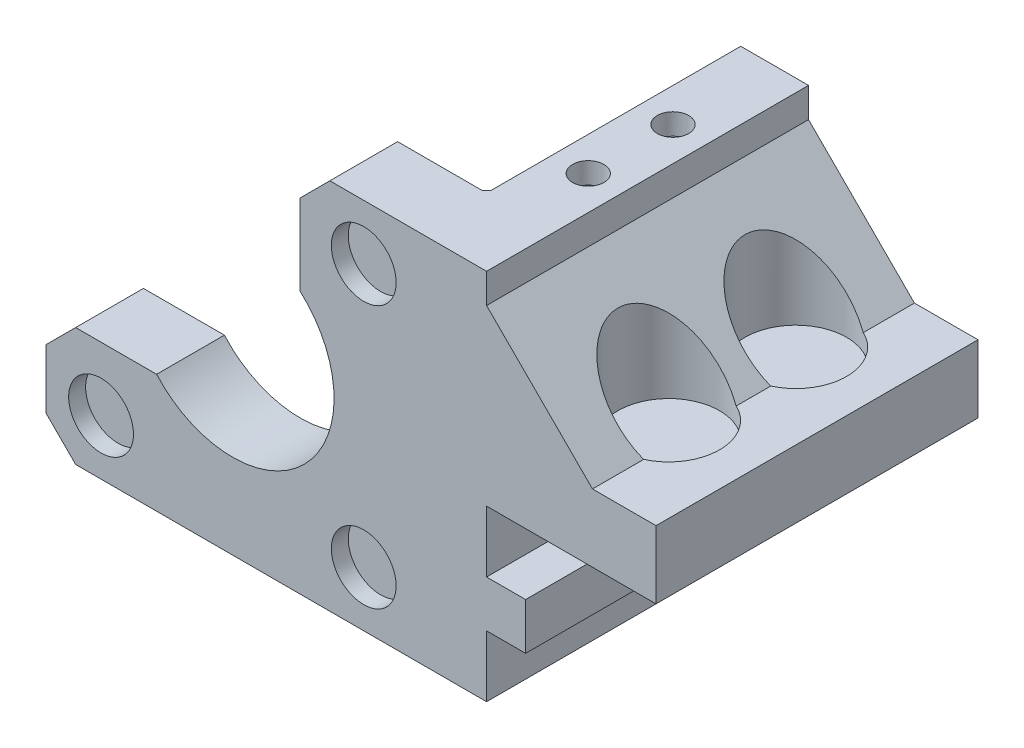
SolidWorks part; units mm, degrees
ref_plane "Front Plane" through (0, 0, 0) normal (0, 0, 1) x (1, 0, 0)
ref_plane "Top Plane" through (0, 0, 0) normal (0, 1, 0) x (1, 0, 0)
ref_plane "Right Plane" through (0, 0, 0) normal (1, 0, 0) x (0, 0, -1)
sketch "Sketch1" plane through (0, 0, 0) normal (0, 0, 1) x (1, 0, 0)
  line L0 (-22, -8) -> (-8.9443, -8)
  line L1 (8, 22) -> (22, 22)
  line L2 (-22, -8) -> (-22, -22)
  line L3 (-22, -22) -> (22, -22)
  line L4 (22, 22) -> (22, -22)
  line L5 (-20, 20) -> (22, -22) construction
  line L6 (-22, -22) -> (22, 22) construction
  line L7 (8, 8.9443) -> (8, 22)
  line L8 (36.9982, -22) -> (31, -22) construction
  arc A0 (-8.9443, -8) -> (8, 8.9443) centre (0, 0) ccw
  circle A1 centre (-15.5, 15.5) radius 1.85 construction
  circle A2 centre (15.5, 15.5) radius 1.85
  circle A3 centre (15.5, -15.5) radius 1.85
  circle A4 centre (-15.5, -15.5) radius 1.85
  dimension "D1" = 3.7
  dimension "D9" = 24
  dimension "D10" = 14
  dimension "D2" = 15.5
  dimension "D3" = 15.5
  dimension "D6" = 31
  dimension "D7" = 31
  dimension "D8" = 44
  dimension "D11" = 22
  dimension "D4" = 2
  dimension "D5" = 2
extrude "Boss-Extrude1" add sketch "Sketch1" along normal blind 8 contours A0 L0 L2 L3 L4 L1 L7 A4 A3 A2
sketch "Sketch3" plane through (0, 0, 8) normal (0, 0, 1) x (1, 0, 0)
  line L0 (30, -9.25) -> (30, -2)
  line L1 (22, -22) -> (30, -22)
  line L2 (22, 22) -> (30, 22)
  line L3 (22, 22) -> (22, 6)
  line L4 (30, -22) -> (30, -14.75)
  line L5 (30, 6) -> (50, 6)
  line L6 (22, 6) -> (22, -22)
  line L7 (30, -2) -> (50, -2)
  line L8 (50, 6) -> (50, -2)
  line L9 (30, -9.25) -> (34.6066, -9.25)
  line L10 (30, 22) -> (30, 6)
  line L12 (30, -14.75) -> (34.6066, -14.75)
  line L13 (34.6066, -9.25) -> (34.6066, -14.75)
  dimension "D1" = 20
  dimension "D2" = 20
  dimension "D3" = 8
  dimension "D4" = 8
  dimension "D5" = 5.5
extrude "Boss-Extrude3" add sketch "Sketch3" against normal blind 38
chamfer "Chamfer1" distance 3.5 angle 45 3 edges at (8, 22, 4) (-22, -8, 4) (-22, -22, 4)
chamfer "Chamfer2" distance 12.5 angle 45 1 edges at (30, 6, -11)
sketch "Sketch4" plane through (0, -2, 0) normal (0, -1, 0) x (1, 0, 0)
  line L3 (50, -30) -> (50, 8) construction
  circle A0 centre (40, -3.5) radius 2.825
  circle A1 centre (40, -18.5) radius 2.825
  point P8 (50, -11)
  dimension "D2" = 5.65
  dimension "D1" = 15
  dimension "D3" = 7.5
extrude "Cut-Extrude1" cut sketch "Sketch4" against normal blind 15
sketch "Sketch5" plane through (0, 6, 0) normal (0, 1, 0) x (1, 0, 0)
  circle A0 centre (40, 18.5) radius 6
  circle A1 centre (40, 3.5) radius 6
  dimension "D1" = 12
extrude "Cut-Extrude2" cut sketch "Sketch5" along normal blind 15 from offset 2 offset against normal yes
chamfer "Chamfer3" distance 0.5 angle 45 1 edges at (22, 0, 0)
sketch "Sketch6" plane through (0, 0, 8) normal (0, 0, 1) x (1, 0, 0)
  circle A0 centre (15.5, 15.5) radius 3.825
  circle A1 centre (15.5, -15.5) radius 3.825
  circle A2 centre (-15.5, -15.5) radius 3.825
  dimension "D1" = 7.65
extrude "Cut-Extrude3" cut sketch "Sketch6" against normal blind 2
sketch "Sketch10" plane through (0, 22, 0) normal (0, 1, 0) x (1, 0, 0)
  line L0 (11.5, 0) -> (21.5, 0) construction
  line L1 (30, 30) -> (30, -8) construction
  circle A0 centre (26, 8) radius 1.85
  circle A1 centre (26, 18) radius 1.85
  dimension "D2" = 3.7
  dimension "D1" = 10
  dimension "D3" = 18
  dimension "D4" = 4
extrude "Cut-Extrude6" cut sketch "Sketch10" against normal blind 10
sketch "Sketch11" plane through (0, 22, 0) normal (0, 1, 0) x (1, 0, 0)
  line L1 (22.4782, 18) -> (24.2391, 14.95) construction
  line L2 (24.2391, 14.95) -> (27.7609, 14.95)
  line L3 (27.7609, 14.95) -> (29.5218, 18)
  line L4 (29.5218, 18) -> (27.7609, 21.05)
  line L5 (27.7609, 21.05) -> (24.2391, 21.05)
  line L6 (24.2391, 21.05) -> (22.4782, 18) construction
  line L7 (22.4782, 8) -> (24.2391, 4.95) construction
  line L8 (24.2391, 4.95) -> (27.7609, 4.95)
  line L9 (27.7609, 4.95) -> (29.5218, 8)
  line L10 (29.5218, 8) -> (27.7609, 11.05)
  line L11 (27.7609, 11.05) -> (24.2391, 11.05)
  line L12 (24.2391, 11.05) -> (22.4782, 8) construction
  line L13 (24.2391, 21.05) -> (20.4884, 21.05)
  line L15 (24.2391, 14.95) -> (20.4884, 14.95)
  line L16 (20.4884, 21.05) -> (20.4884, 14.95)
  line L17 (24.2391, 11.05) -> (20.4884, 11.05)
  line L19 (24.2391, 4.95) -> (20.4884, 4.95)
  line L20 (20.4884, 11.05) -> (20.4884, 4.95)
  circle A0 centre (26, 18) radius 3.05 construction
  circle A1 centre (26, 8) radius 3.05 construction
  dimension "D1" = 6.1
extrude "Cut-Extrude7" cut sketch "Sketch11" against normal blind 2.8 from offset 2.5 offset against normal yes
sketch "Sketch12" plane through (0, 4, 0) normal (0, 1, 0) x (1, 0, 0)
  circle A0 centre (40, 3.5) radius 3.9401
  circle A1 centre (40, 18.5) radius 4.7657
extrude "print_helper" add sketch "Sketch12" against normal blind 0.65
sketch "Sketch7" plane through (0, 0, 6) normal (0, 0, 1) x (1, 0, 0)
  circle A0 centre (15.5, 15.5) radius 2.5463
  circle A1 centre (15.5, -15.5) radius 2.7624
  circle A2 centre (-15.5, -15.5) radius 2.986
extrude "print_helper1" add sketch "Sketch7" against normal blind 0.65
